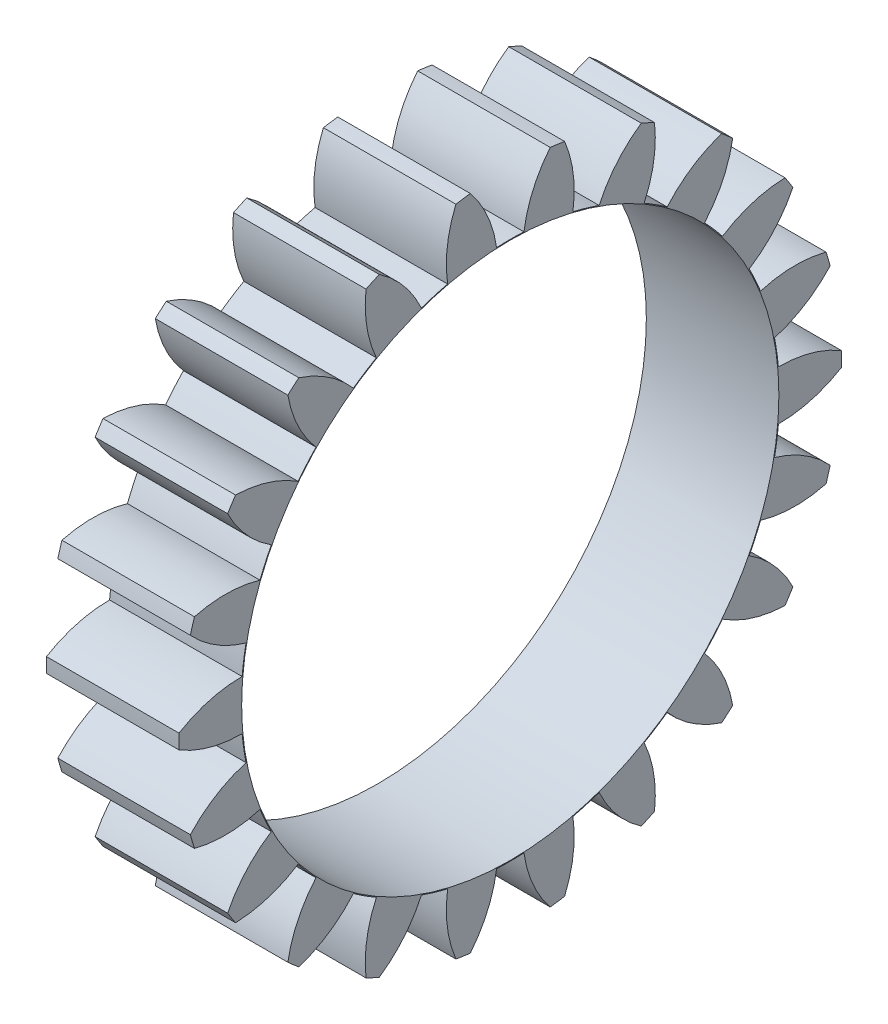
SolidWorks part; units mm, degrees
ref_plane "Plane1" through (0, 0, 0) normal (0, 0, 1) x (1, 0, 0)
ref_plane "Plane2" through (0, 0, 0) normal (0, 1, 0) x (1, 0, 0)
ref_plane "Plane3" through (0, 0, 0) normal (1, 0, 0) x (0, 0, -1)
other "Configuration Table"
sketch "HoldingSke" plane through (0, 0, 0) normal (0, 1, 0) x (1, 0, 0)
  line L0 (0, 0) -> (565.2113, -228.3602)
  line L1 (-15, 0) -> (100, 0) construction
  line L2 (0, 0) -> (-2.1039, 2.3779)
  line L3 (0, 0) -> (-11.863, 4.5341)
  line L4 (0, 0) -> (8.0072, 3.2351)
  line L5 (0, 0) -> (-47.5972, -17.7524)
  line L6 (0, 0) -> (-4.2111, -2.8413)
  line L7 (-2.1039, 2.3779) -> (8.8308, 51.9871)
  line L8 (-76.2, 54.61) -> (-47.9044, 54.61)
  line L9 (-71.009, 38.7566) -> (-53.1078, 45.2721)
  line L10 (-76.2, 71.12) -> (104.1128, 71.12)
  line L11 (0, 0) -> (-5.08, 0)
  line L12 (-76.2, 101.6) -> (-76.1573, 101.6)
  line L13 (24.9733, 27.94) -> (52.9518, 28.4284)
  line L14 (24.9733, 27.94) -> (25.0241, 27.9398)
  line L15 (24.9733, 27.94) -> (100.4021, 29.52)
  circle A0 centre (0, 0) radius 12.7
  circle A1 centre (0, 0) radius 10.3209
  circle A2 centre (0, 0) radius 38.1
  circle A3 centre (0, 0) radius 10.2955
  dimension "MHD" = 20.6417
  dimension "Hub_dia" = 76.2
  dimension "Bore" = 25.4
  dimension "MBD" = 20.5909
  dimension "Num_teeth" = 22
  dimension "Pitch" = 609.6
  dimension "Overall_len" = 50.8
  dimension "Show_teeth" = 22
  dimension "Thickness" = 5.08
  dimension "OAL" = 50.8001
  dimension "T_dim" = 28.2956
  dimension "Ap" = 20
  dimension "H" = 19.05
  dimension "Pitch_radius" = 180.3128
  dimension "Width" = 5.08
  dimension "Backlash" = 0.0427
  dimension "Addendum_fac" = 1
  dimension "Dedendum_fac" = 1.2
  dimension "Clearance_fac" = 0.2
  dimension "Dedendum_add" = 0.0508
sketch "BasProSke" plane through (0, 0, 0) normal (0, 1, 0) x (1, 0, 0)
  line L0 (-10, 0) -> (60, 0) construction
  line L1 (0, 0) -> (0, 12.7)
  line L2 (0, 0) -> (5.08, 0)
  line L3 (5.08, 0) -> (5.08, 12.7)
  line L4 (5.08, 12.7) -> (0, 12.7)
  dimension "Thickness" = 5.08
  dimension "Diameter" = 25.4
revolve "Base-Revolve" add sketch "BasProSke" angle 360 about L0
sketch "TooCutSke" plane through (0, 0, 0) normal (1, 0, 0) x (0, 0, -1)
  line L1 (0, 0) -> (0, 107) construction
  line L2 (0, 0) -> (-0.9051, 11.6064) construction
  line L3 (0, 0) -> (-3.3066, 22.9977) construction
  line L4 (-0.9051, 11.6064) -> (-1.6533, 11.4989) construction
  arc A0 (0.5239, 10.3076) -> (-0.5239, 10.3076) centre (0, 0) ccw
  arc A1 (1.5497, 12.6307) -> (-1.5497, 12.6307) centre (0, 0) ccw
  circle A2 centre (0, 0) radius 11.6417 construction
  circle A3 centre (0, 0) radius 10.9396 construction
  arc A4 (-0.5239, 10.3076) -> (-1.5497, 12.6307) centre (-5.1352, 9.6594) ccw
  arc A5 (1.5497, 12.6307) -> (0.5239, 10.3076) centre (5.1352, 9.6594) ccw
  dimension "Root_dia" = 20.6417
  dimension "Overcut_dia" = 25.4508
  dimension "Pitch_dia" = 23.2833
  dimension "Base_dia" = 21.8792
  dimension "Flank_rad" = 4.6567
  dimension "Half_ang" = 8.182
  dimension "Half_CT" = 0.7558
extrude "ToothCut" cut sketch "TooCutSke" along normal through all
fillet "Breaks" [suppressed] radius 0.0212
fillet "RootFillets" [suppressed] radius 0.2625
pattern_circular "TeethCuts" count 22 every 16.364 about axis through (-10, 0, 0) along (1, 0, 0) of "ToothCut", "RootFillets", "Breaks"
sketch "HubNeaOneSke" plane through (0, 0, 0) normal (-1, 0, 0) x (0, 0, 1)
  circle A0 centre (0, 0) radius 10.3209
  dimension "Diameter" = 20.6417
extrude "HubNearOne" [suppressed] add sketch "HubNeaOneSke" along normal blind 45.7201
sketch "HubNeaBotSke" plane through (0, 0, 0) normal (-1, 0, 0) x (0, 0, 1)
  circle A0 centre (0, 0) radius 10.3209
  dimension "Diameter" = 20.6417
extrude "HubNearBoth" [suppressed] add sketch "HubNeaBotSke" along normal blind 22.86
ref_plane "FarPln" through (5.08, 0, 0) normal (1, 0, 0) x (0, 0, -1)
sketch "HubFarSke" plane through (5.08, 0, 0) normal (1, 0, 0) x (0, 0, -1)
  circle A0 centre (0, 0) radius 10.3209
  dimension "Diameter" = 20.6417
extrude "HubFar" [suppressed] add sketch "HubFarSke" along normal blind 22.86
sketch "BorSke" plane through (0, 0, 0) normal (1, 0, 0) x (0, 0, -1)
  circle A0 centre (0, 0) radius 10.2955
  dimension "Diameter" = 20.5909
extrude "Bore" cut sketch "BorSke" along normal mid plane 101.6001
sketch "KeySke" plane through (0, 0, 0) normal (1, 0, 0) x (0, 0, -1)
  line L0 (-3.175, 0) -> (-3.175, 18.0001)
  line L1 (-3.175, 18.0001) -> (3.175, 18.0001)
  line L2 (3.175, 18.0001) -> (3.175, 0)
  line L3 (0, 0) -> (0, 34) construction
  line L4 (-3.175, 0) -> (3.175, 0)
  dimension "Offset" = 18.0001
  dimension "Width" = 6.35
extrude "Keyway" [suppressed] cut sketch "KeySke" along normal mid plane 101.6001
pattern_circular "Keyway2" [suppressed] count 2 every 90 about axis through (-10, 0, 0) along (1, 0, 0)
equation "' \"Pitch@HoldingSke\" = 4"
equation "' \"Num_teeth@HoldingSke\" = 12"
equation "' \"Ap@HoldingSke\" =  20"
equation "' \"Ap@HoldingSke\" = 20"
equation "' \"Width@HoldingSke\" = 0.5"
equation "' \"Hub_dia@HoldingSke\"= 1"
equation "' \"Hub_dia@HoldingSke\" = 1"
equation "' \"Overall_len@HoldingSke\" = 1.0"
equation "' \"Bore@HoldingSke\" = 0.75"
equation "' \"T_dim@HoldingSke\" = 0.85"
equation "' \"Width@KeySke\" = 0.25"
equation "' \"Show_teeth@HoldingSke\" = 13"
equation "' \"Backlash@HoldingSke\" = 0.009"
equation "' \"Addendum_fac@HoldingSke\" = 1.0"
equation "' \"Dedendum_fac@HoldingSke\" = 1.25"
equation "' \"Dedendum_add@HoldingSke\" = 0.00005"
equation "' \"Clearance_fac@HoldingSke\" = 0.25"
equation "' \"Pitch@HoldingSke\" = 0.5"
equation "' \"Num_teeth@HoldingSke\" = 23"
equation "' \"Show_teeth@HoldingSke\" = 23"
equation "' \"Backlash@HoldingSke\" = 0.0375"
equation "\"Overcut_dia@TooCutSke\" = (\"Num_teeth@HoldingSke\" + 2 * \"Addendum_fac@HoldingSke\") / \"Pitch@HoldingSke\" + 0.002"
equation "\"Pitch_dia@TooCutSke\" = \"Num_teeth@HoldingSke\" / \"Pitch@HoldingSke\""
equation "\"Base_dia@TooCutSke\" = \"Num_teeth@HoldingSke\" / \"Pitch@HoldingSke\" * cos((\"Ap@HoldingSke\"  * 3.14159265 / 180))"
equation "\"Root_dia@TooCutSke\" = (\"Num_teeth@HoldingSke\" + 2) / \"Pitch@HoldingSke\" - 2 * (\"Addendum_fac@HoldingSke\" + \"Dedendum_fac@HoldingSke\") / \"Pitch@HoldingSke\" - \"Dedendum_add@HoldingSke\" * 2"
equation "\"Half_ang@TooCutSke\" = 180 / \"Num_teeth@HoldingSke\""
equation "\"Half_CT@TooCutSke\" = \"Num_teeth@HoldingSke\" / \"Pitch@HoldingSke\" * sin((3.14159265 / 2 / \"Num_teeth@HoldingSke\")) / 2 - 7 * \"Backlash@HoldingSke\" / 4"
equation "\"Flank_rad@TooCutSke\" = \"Num_teeth@HoldingSke\" / \"Pitch@HoldingSke\" / 5"
equation "\"Radius@RootFillets\" = \"Clearance_fac@HoldingSke\" / \"Pitch@HoldingSke\" + \"Dedendum_add@HoldingSke\""
equation "\"Break_rad@Breaks\" = 0.02 / \"Pitch@HoldingSke\""
equation "\"Thickness@HoldingSke\" = \"Width@HoldingSke\""
equation "\"OAL@HoldingSke\" = \"Thickness@HoldingSke\""
equation "\"MHD@HoldingSke\" = (\"Num_teeth@HoldingSke\" + 2) / \"Pitch@HoldingSke\" - 2 * (\"Addendum_fac@HoldingSke\" + \"Dedendum_fac@HoldingSke\")  / \"Pitch@HoldingSke\" - \"Dedendum_add@HoldingSke\" * 2"
equation "\"MBD@HoldingSke\" = (\"Num_teeth@HoldingSke\" + 2) / \"Pitch@HoldingSke\" - 2 * (\"Addendum_fac@HoldingSke\" + \"Dedendum_fac@HoldingSke\")  / \"Pitch@HoldingSke\" - \"Dedendum_add@HoldingSke\" * 2 - 0.002"
equation "\"MHD@HoldingSke\" = ((sgn( \"MHD@HoldingSke\" - \"Hub_dia@HoldingSke\" )-1)*( \"MHD@HoldingSke\" - \"Hub_dia@HoldingSke\" ))/-2+ \"Hub_dia@HoldingSke\""
equation "\"MBD@HoldingSke\" = ((sgn( \"MBD@HoldingSke\" - \"Bore@HoldingSke\" )-1)*( \"MBD@HoldingSke\" - \"Bore@HoldingSke\" ))/-2+ \"Bore@HoldingSke\""
equation "\"OAL@HoldingSke\" = ((sgn( \"OAL@HoldingSke\" - \"Overall_len@HoldingSke\" )+1)*( \"OAL@HoldingSke\" - \"Overall_len@HoldingSke\" ))/2 + \"Overall_len@HoldingSke\" + 0.000002"
equation "\"Num_teeth@TeethCuts\" = int( \"Show_teeth@HoldingSke\" ) + 1"
equation "\"Num_teeth@TeethCuts\" = ((sgn( \"Num_teeth@TeethCuts\" - \"Num_teeth@HoldingSke\" )-1)*( \"Num_teeth@TeethCuts\" - \"Num_teeth@HoldingSke\" ))/-2+ \"Num_teeth@HoldingSke\""
equation "\"Num_teeth@TeethCuts\" = ((sgn( \"Num_teeth@TeethCuts\" - 2.0)+1)*( \"Num_teeth@TeethCuts\" - 2.0))/2 +2.0"
equation "\"Angle@TeethCuts\" = 360.0 / \"Num_teeth@HoldingSke\""
equation "\"Diameter@BasProSke\" = (\"Num_teeth@HoldingSke\" + 2 * \"Addendum_fac@HoldingSke\") / \"Pitch@HoldingSke\""
equation "\"Thickness@BasProSke\"  = \"Thickness@HoldingSke\""
equation "' \"Fillet_rad@BasProSke\" =  \"Thickness@HoldingSke\" * 0.05"
equation "' \"Fillet_rad@BasProSke\" = \"Thickness@HoldingSke\" * 0.05"
equation "\"MHD@HoldingSke\" = ((sgn( \"MHD@HoldingSke\" - \"Root_dia@TooCutSke\" )-1)*( \"MHD@HoldingSke\" - \"Root_dia@TooCutSke\" ))/-2+ \"Root_dia@TooCutSke\""
equation "\"Diameter@HubNeaOneSke\" = \"MHD@HoldingSke\""
equation "\"Length@HubNearOne\" = \"OAL@HoldingSke\" - \"Thickness@BasProSke\""
equation "\"Diameter@HubNeaBotSke\" = \"MHD@HoldingSke\""
equation "\"Length@HubNearBoth\" = ( \"OAL@HoldingSke\" - \"Thickness@BasProSke\" ) / 2.0"
equation "\"Thickness@FarPln\" = \"Thickness@BasProSke\""
equation "\"Diameter@HubFarSke\" = \"MHD@HoldingSke\""
equation "\"Length@HubFar\" = ( \"OAL@HoldingSke\" - \"Thickness@BasProSke\" ) / 2.0"
equation "\"Diameter@BorSke\" = \"MBD@HoldingSke\""
equation "\"D1@Bore\" = \"OAL@HoldingSke\" * 2.0"
equation "\"D1@Keyway\" = \"OAL@HoldingSke\" * 2.0"
equation "\"Offset@KeySke\" = \"T_dim@HoldingSke\" - \"MBD@HoldingSke\" / 2.0"
